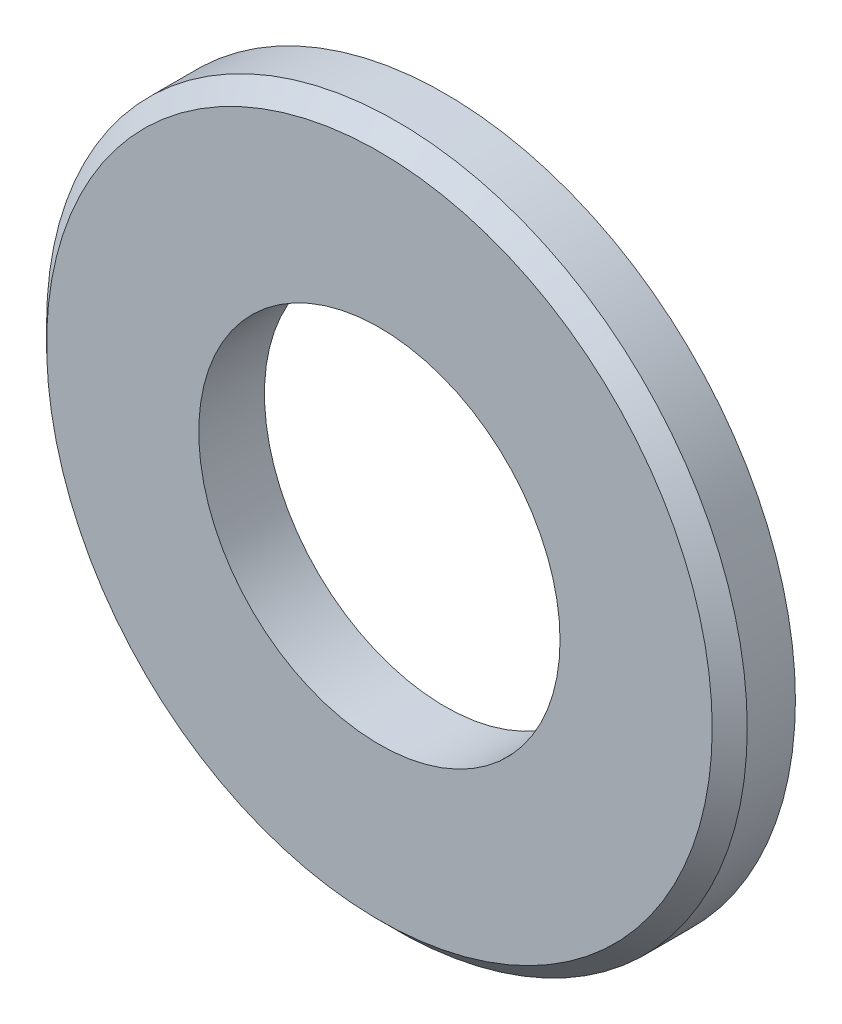
SolidWorks part; units mm, degrees
ref_plane "Plane1" through (0, 0, 0) normal (0, 0, 1) x (1, 0, 0)
ref_plane "Plane2" through (0, 0, 0) normal (0, 1, 0) x (1, 0, 0)
ref_plane "Plane3" through (0, 0, 0) normal (1, 0, 0) x (0, 0, -1)
sketch "Эскиз1" plane through (0, 0, 0) normal (0, 0, 1) x (1, 0, 0)
  circle A0 centre (10.9282, 3.9727) radius 8.25
  circle A1 centre (10.9282, 3.9727) radius 16
  dimension "D1" = 32
  dimension "D2" = 16.5
extrude "Основание-Вытянуть" add sketch "Эскиз1" along normal blind 3
chamfer "Фаска1" distance 0.8 angle 45
